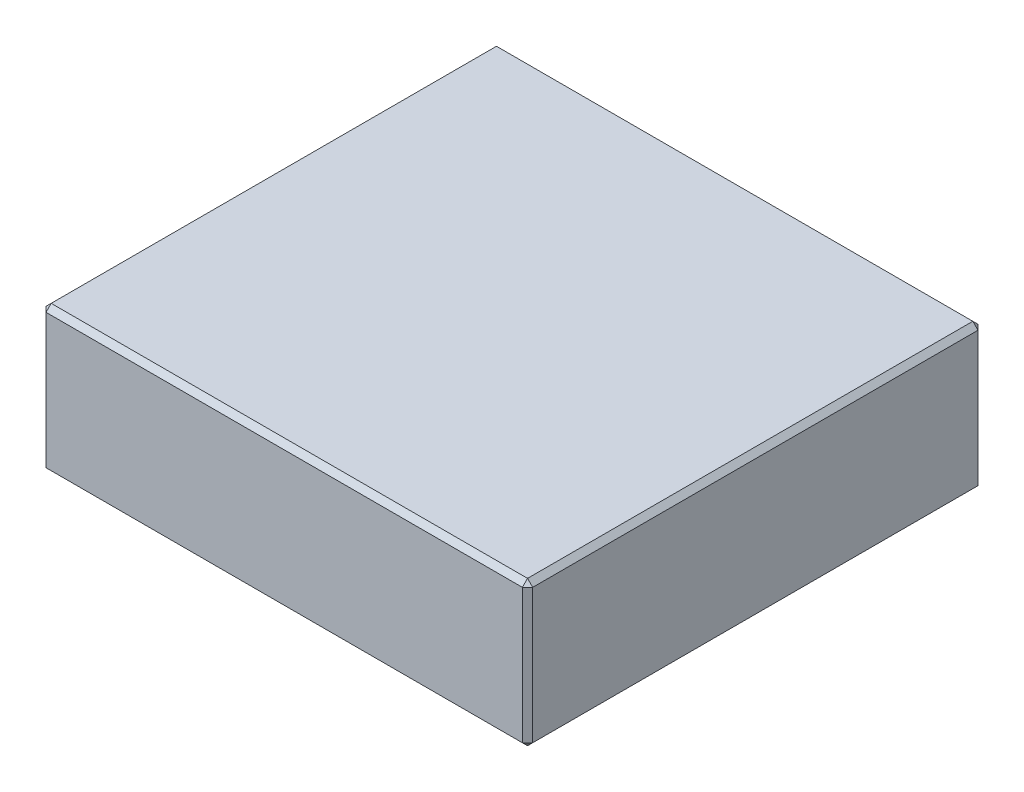
SolidWorks part; units mm, degrees
ref_plane "前视基准面" through (0, 0, 0) normal (0, 0, 1) x (1, 0, 0)
ref_plane "上视基准面" through (0, 0, 0) normal (0, 1, 0) x (1, 0, 0)
ref_plane "右视基准面" through (0, 0, 0) normal (1, 0, 0) x (0, 0, -1)
sketch "草图1" plane through (0, 0, 0) normal (0, 1, 0) x (1, 0, 0)
  line L0 (0, 0) -> (23.5, 0) construction
  line L1 (0, 0) -> (0, 22) construction
  line L2 (-23.5, 22) -> (23.5, 22)
  line L3 (23.5, 22) -> (23.5, -22)
  line L4 (-23.5, -22) -> (23.5, -22)
  line L5 (-23.5, 22) -> (-23.5, -22)
  point P9 (0, -22)
extrude "凸台-拉伸1" add sketch "草图1" along normal blind 14
chamfer "倒角1" distance 0.5 angle 45 12 edges at (23.5, 14, 0) (-23.5, 0, 0) (0, 0, 22) (23.5, 0, 0) (0, 0, -22) (-23.5, 7, -22) (-23.5, 7, 22) (23.5, 7, -22) (23.5, 7, 22) (0, 14, -22) (-23.5, 14, 0) (0, 14, 22)
